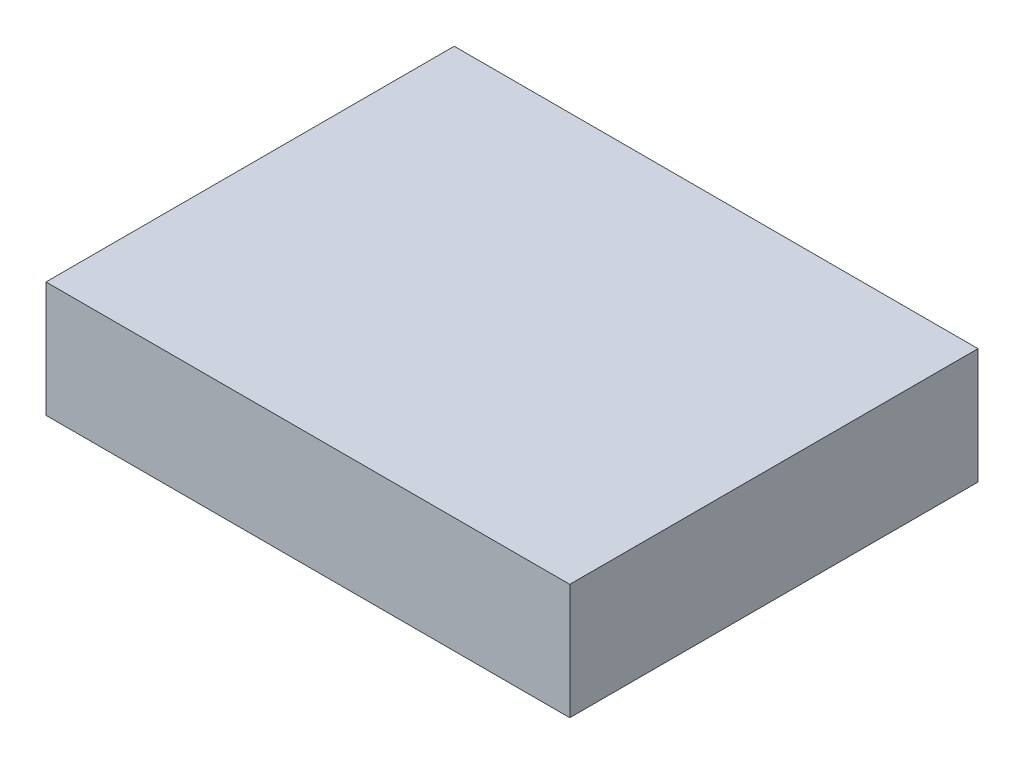
SolidWorks part; units mm, degrees
ref_plane "Front Plane" through (0, 0, 0) normal (0, 0, 1) x (1, 0, 0)
ref_plane "Top Plane" through (0, 0, 0) normal (0, 1, 0) x (1, 0, 0)
ref_plane "Right Plane" through (0, 0, 0) normal (1, 0, 0) x (0, 0, -1)
sketch "Sketch1" plane through (0, 0, 0) normal (0, 1, 0) x (1, 0, 0)
  line L1 (-34, -26.5) -> (34, -26.5)
  line L2 (-34, -26.5) -> (-34, 26.5)
  line L3 (-34, 26.5) -> (34, 26.5)
  line L4 (34, -26.5) -> (34, 26.5)
  line L5 (-34, -26.5) -> (34, 26.5) construction
  line L6 (-34, 26.5) -> (34, -26.5) construction
  point P0 (0, 0)
  dimension "D1" = 68
  dimension "D2" = 53
extrude "Boss-Extrude1" add sketch "Sketch1" along normal blind 15
